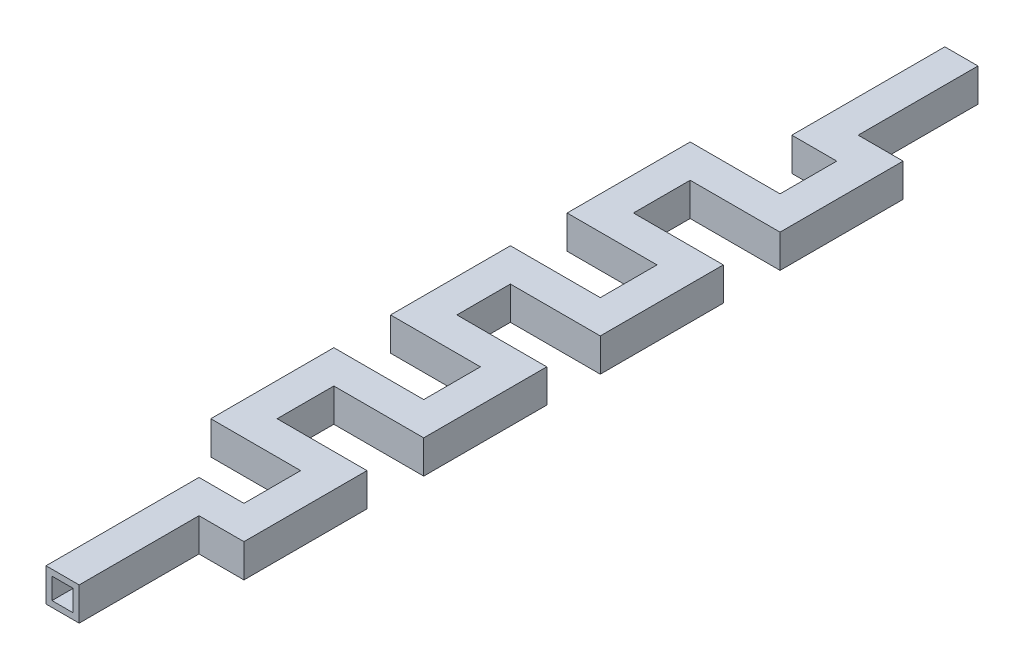
SolidWorks part; units mm, degrees
ref_plane "Front Plane" through (0, 0, 0) normal (0, 0, 1) x (1, 0, 0)
ref_plane "Top Plane" through (0, 0, 0) normal (0, 1, 0) x (1, 0, 0)
ref_plane "Right Plane" through (0, 0, 0) normal (1, 0, 0) x (0, 0, -1)
sketch "Sketch3" plane through (0, 0, 0) normal (0, 0, 1) x (1, 0, 0)
  line L1 (-1.3836, -1.3836) -> (1.3836, -1.3836)
  line L2 (-1.3836, -1.3836) -> (-1.3836, 1.3836)
  line L3 (-1.3836, 1.3836) -> (1.3836, 1.3836)
  line L4 (1.3836, -1.3836) -> (1.3836, 1.3836)
  line L5 (-1.3836, -1.3836) -> (1.3836, 1.3836) construction
  line L6 (-1.3836, 1.3836) -> (1.3836, -1.3836) construction
  point P0 (0, 0)
  dimension "D1" = 2.7671
  dimension "D2" = 2.7671
extrude "Boss-Extrude1" add sketch "Sketch3" along normal mid plane 10
sketch "Sketch4" plane through (1.3836, 0, 0) normal (1, 0, 0) x (0, 0, -1)
  line L1 (-2.2329, -1.3836) -> (-5, -1.3836)
  line L2 (-2.2329, -1.3836) -> (-2.2329, 1.3836)
  line L3 (-2.2329, 1.3836) -> (-5, 1.3836)
  line L4 (-5, -1.3836) -> (-5, 1.3836)
  line L5 (-2.2329, -1.3836) -> (-5, 1.3836) construction
  line L6 (-2.2329, 1.3836) -> (-5, -1.3836) construction
  line L7 (2.2329, -1.3836) -> (5, -1.3836)
  line L8 (2.2329, -1.3836) -> (2.2329, 1.3836)
  line L9 (2.2329, 1.3836) -> (5, 1.3836)
  line L10 (5, -1.3836) -> (5, 1.3836)
  line L11 (2.2329, -1.3836) -> (5, 1.3836) construction
  line L12 (2.2329, 1.3836) -> (5, -1.3836) construction
  point P0 (-3.6164, 0)
  point P6 (3.6164, 0)
  dimension "D1" = 2.7671
  dimension "D2" = 2.7672
  dimension "D3" = 2.7671
  dimension "D4" = 2.7672
extrude "Boss-Extrude2" add sketch "Sketch4" along normal blind 7.5
sketch "Sketch5" plane through (0, 0, 5) normal (0, 0, 1) x (1, 0, 0)
  line L1 (6.1164, -1.3836) -> (8.8836, -1.3836)
  line L2 (6.1164, -1.3836) -> (6.1164, 1.3836)
  line L3 (6.1164, 1.3836) -> (8.8836, 1.3836)
  line L4 (8.8836, -1.3836) -> (8.8836, 1.3836)
  line L5 (6.1164, -1.3836) -> (8.8836, 1.3836) construction
  line L6 (6.1164, 1.3836) -> (8.8836, -1.3836) construction
  point P0 (7.5, 0)
  dimension "D1" = 2.7671
extrude "Boss-Extrude3" add sketch "Sketch5" along normal blind 7.5
sketch "Sketch6" plane through (6.1164, 0, 0) normal (-1, 0, 0) x (0, 0, 1)
  line L1 (9.7329, -1.3836) -> (12.5, -1.3836)
  line L2 (9.7329, -1.3836) -> (9.7329, 1.3836)
  line L3 (9.7329, 1.3836) -> (12.5, 1.3836)
  line L4 (12.5, -1.3836) -> (12.5, 1.3836)
  line L5 (9.7329, -1.3836) -> (12.5, 1.3836) construction
  line L6 (9.7329, 1.3836) -> (12.5, -1.3836) construction
  point P0 (11.1164, 0)
  dimension "D1" = 2.7671
extrude "Boss-Extrude4" add sketch "Sketch6" along normal blind 7.5
sketch "Sketch7" plane through (0, 0, 12.5) normal (0, 0, 1) x (1, 0, 0)
  line L1 (-1.3836, -1.3836) -> (1.3836, -1.3836)
  line L2 (-1.3836, -1.3836) -> (-1.3836, 1.3836)
  line L3 (-1.3836, 1.3836) -> (1.3836, 1.3836)
  line L4 (1.3836, -1.3836) -> (1.3836, 1.3836)
  line L5 (-1.3836, -1.3836) -> (1.3836, 1.3836) construction
  line L6 (-1.3836, 1.3836) -> (1.3836, -1.3836) construction
  point P0 (0, 0)
extrude "Boss-Extrude5" add sketch "Sketch7" along normal blind 7.5
sketch "Sketch8" plane through (0, 0, -5) normal (0, 0, -1) x (-1, 0, 0)
  line L0 (-8.8836, 1.3836) -> (1.3836, 1.3836) construction
  line L1 (-8.8836, -1.3836) -> (-6.1164, -1.3836)
  line L2 (-8.8836, -1.3836) -> (-8.8836, 1.3836)
  line L3 (-8.8836, 1.3836) -> (-6.1164, 1.3836)
  line L4 (-6.1164, -1.3836) -> (-6.1164, 1.3836)
  line L5 (-8.8836, -1.3836) -> (-6.1164, 1.3836) construction
  line L6 (-8.8836, 1.3836) -> (-6.1164, -1.3836) construction
  line L7 (-8.8836, -1.3836) -> (-8.8836, 1.3836) construction
  point P0 (-7.5, 0)
  dimension "D1" = 2.7671
  dimension "D2" = 1.3836
extrude "Boss-Extrude6" add sketch "Sketch8" along normal blind 7.5
sketch "Sketch9" plane through (6.1164, 0, 0) normal (-1, 0, 0) x (0, 0, 1)
  line L1 (-9.7329, -1.3836) -> (-12.5, -1.3836)
  line L2 (-9.7329, -1.3836) -> (-9.7329, 1.3836)
  line L3 (-9.7329, 1.3836) -> (-12.5, 1.3836)
  line L4 (-12.5, -1.3836) -> (-12.5, 1.3836)
  line L5 (-9.7329, -1.3836) -> (-12.5, 1.3836) construction
  line L6 (-9.7329, 1.3836) -> (-12.5, -1.3836) construction
  point P0 (-11.1164, 0)
  dimension "D1" = 2.7671
extrude "Boss-Extrude7" add sketch "Sketch9" along normal blind 7.5
sketch "Sketch10" plane through (0, 0, -12.5) normal (0, 0, -1) x (-1, 0, 0)
  line L1 (-1.3836, -1.3836) -> (1.3836, -1.3836)
  line L2 (-1.3836, -1.3836) -> (-1.3836, 1.3836)
  line L3 (-1.3836, 1.3836) -> (1.3836, 1.3836)
  line L4 (1.3836, -1.3836) -> (1.3836, 1.3836)
  line L5 (-1.3836, -1.3836) -> (1.3836, 1.3836) construction
  line L6 (-1.3836, 1.3836) -> (1.3836, -1.3836) construction
  point P0 (0, 0)
extrude "Boss-Extrude8" add sketch "Sketch10" along normal blind 7.5
sketch "Sketch11" plane through (1.3836, 0, 0) normal (1, 0, 0) x (0, 0, -1)
  line L1 (17.2329, -1.3836) -> (20, -1.3836)
  line L2 (17.2329, -1.3836) -> (17.2329, 1.3836)
  line L3 (17.2329, 1.3836) -> (20, 1.3836)
  line L4 (20, -1.3836) -> (20, 1.3836)
  line L5 (17.2329, -1.3836) -> (20, 1.3836) construction
  line L6 (17.2329, 1.3836) -> (20, -1.3836) construction
  line L7 (-17.2329, -1.3836) -> (-20, -1.3836)
  line L8 (-17.2329, -1.3836) -> (-17.2329, 1.3836)
  line L9 (-17.2329, 1.3836) -> (-20, 1.3836)
  line L10 (-20, -1.3836) -> (-20, 1.3836)
  line L11 (-17.2329, -1.3836) -> (-20, 1.3836) construction
  line L12 (-17.2329, 1.3836) -> (-20, -1.3836) construction
  point P0 (18.6164, 0)
  point P6 (-18.6164, 0)
  dimension "D1" = 2.7671
  dimension "D2" = 2.7672
  dimension "D3" = 2.7671
  dimension "D4" = 2.7672
extrude "Boss-Extrude9" add sketch "Sketch11" along normal blind 7.5
sketch "Sketch12" plane through (0, 0, -20) normal (0, 0, -1) x (-1, 0, 0)
  line L0 (-8.8836, -1.3836) -> (-8.8836, 1.3836) construction
  line L1 (-6.1164, -1.3836) -> (-8.8836, -1.3836)
  line L2 (-6.1164, -1.3836) -> (-6.1164, 1.3836)
  line L3 (-6.1164, 1.3836) -> (-8.8836, 1.3836)
  line L4 (-8.8836, -1.3836) -> (-8.8836, 1.3836)
  line L5 (-6.1164, -1.3836) -> (-8.8836, 1.3836) construction
  line L6 (-6.1164, 1.3836) -> (-8.8836, -1.3836) construction
  point P0 (-7.5, 0)
  dimension "D1" = 2.7671
  dimension "D2" = 2.7672
extrude "Boss-Extrude10" add sketch "Sketch12" along normal blind 7.5
sketch "Sketch13" plane through (6.1164, 0, 0) normal (-1, 0, 0) x (0, 0, 1)
  line L1 (-24.7328, -1.3836) -> (-27.5, -1.3836)
  line L2 (-24.7328, -1.3836) -> (-24.7328, 1.3836)
  line L3 (-24.7328, 1.3836) -> (-27.5, 1.3836)
  line L4 (-27.5, -1.3836) -> (-27.5, 1.3836)
  line L5 (-24.7328, -1.3836) -> (-27.5, 1.3836) construction
  line L6 (-24.7328, 1.3836) -> (-27.5, -1.3836) construction
  point P0 (-26.1164, 0)
  dimension "D1" = 2.7671
extrude "Boss-Extrude11" add sketch "Sketch13" along normal blind 3.75
sketch "Sketch14" plane through (0, 0, -27.5) normal (0, 0, -1) x (-1, 0, 0)
  line L0 (-2.3664, 1.3836) -> (-8.8836, 1.3836) construction
  line L1 (-5.1336, -1.3836) -> (-2.3664, -1.3836)
  line L2 (-5.1336, -1.3836) -> (-5.1336, 1.3836)
  line L3 (-5.1336, 1.3836) -> (-2.3664, 1.3836)
  line L4 (-2.3664, -1.3836) -> (-2.3664, 1.3836)
  line L5 (-5.1336, -1.3836) -> (-2.3664, 1.3836) construction
  line L6 (-5.1336, 1.3836) -> (-2.3664, -1.3836) construction
  line L7 (-2.3664, 1.3836) -> (-2.3664, -1.3836) construction
  line L8 (-8.8836, -1.3836) -> (-2.3664, -1.3836) construction
  point P0 (-3.75, 0)
  dimension "D1" = 0
  dimension "D2" = 2.7671
  dimension "D3" = 0
extrude "Boss-Extrude12" add sketch "Sketch14" along normal blind 10
sketch "Sketch15" plane through (0, 0, 20) normal (0, 0, 1) x (1, 0, 0)
  line L1 (6.1164, -1.3836) -> (8.8836, -1.3836)
  line L2 (6.1164, -1.3836) -> (6.1164, 1.3836)
  line L3 (6.1164, 1.3836) -> (8.8836, 1.3836)
  line L4 (8.8836, -1.3836) -> (8.8836, 1.3836)
  line L5 (6.1164, -1.3836) -> (8.8836, 1.3836) construction
  line L6 (6.1164, 1.3836) -> (8.8836, -1.3836) construction
  point P0 (7.5, 0)
  dimension "D1" = 2.7671
extrude "Boss-Extrude13" add sketch "Sketch15" along normal blind 7.5
sketch "Sketch16" plane through (6.1164, 0, 0) normal (-1, 0, 0) x (0, 0, 1)
  line L1 (24.7328, -1.3836) -> (27.5, -1.3836)
  line L2 (24.7328, -1.3836) -> (24.7328, 1.3836)
  line L3 (24.7328, 1.3836) -> (27.5, 1.3836)
  line L4 (27.5, -1.3836) -> (27.5, 1.3836)
  line L5 (24.7328, -1.3836) -> (27.5, 1.3836) construction
  line L6 (24.7328, 1.3836) -> (27.5, -1.3836) construction
  point P0 (26.1164, 0)
  dimension "D1" = 2.7671
extrude "Boss-Extrude14" add sketch "Sketch16" along normal blind 3.75
sketch "Sketch17" plane through (0, 0, 27.5) normal (0, 0, 1) x (1, 0, 0)
  line L0 (6.1164, 1.3836) -> (-1.3836, 1.3836) construction
  line L1 (5.1336, -1.3836) -> (2.3664, -1.3836)
  line L2 (5.1336, -1.3836) -> (5.1336, 1.3836)
  line L3 (5.1336, 1.3836) -> (2.3664, 1.3836)
  line L4 (2.3664, -1.3836) -> (2.3664, 1.3836)
  line L5 (5.1336, -1.3836) -> (2.3664, 1.3836) construction
  line L6 (5.1336, 1.3836) -> (2.3664, -1.3836) construction
  point P0 (3.75, 0)
  dimension "D1" = 2.7671
extrude "Boss-Extrude15" add sketch "Sketch17" along normal blind 10
sketch "Sketch23" plane through (0, 1.3836, 0) normal (0, 1, 0) x (1, 0, 0)
  line L0 (2.8664, 37.5) -> (4.6336, 37.5)
  line L1 (2.3664, 37.5) -> (5.1336, 37.5) construction
  line L2 (4.6336, 37.5) -> (4.6336, 27)
  line L3 (4.6336, 27) -> (8.3836, 27)
  line L4 (8.3836, 27) -> (8.3836, 17.7329)
  line L5 (8.3836, 17.7329) -> (0.8836, 17.7329)
  line L6 (0.8836, 17.7329) -> (0.8836, 12)
  line L7 (0.8836, 12) -> (8.3836, 12)
  line L8 (8.3836, 12) -> (8.3836, 2.7329)
  line L9 (8.3836, 2.7329) -> (0.8836, 2.7328)
  line L10 (0.8836, 2.7328) -> (0.8836, -2.7329)
  line L11 (0.8836, -2.7329) -> (8.3836, -2.7329)
  line L12 (8.3836, -2.7329) -> (8.3836, -12)
  line L13 (8.3836, -12) -> (0.8836, -12)
  line L14 (0.8836, -12) -> (0.8836, -17.7329)
  line L15 (0.8836, -17.7329) -> (8.3836, -17.7329)
  line L16 (8.3836, -17.7329) -> (8.3836, -27)
  line L17 (8.3836, -27) -> (4.6336, -27)
  line L18 (4.6336, -27) -> (4.6336, -37.5)
  line L19 (5.1336, -37.5) -> (2.3664, -37.5) construction
  line L20 (4.6336, -37.5) -> (2.8664, -37.5)
  line L21 (2.8664, -37.5) -> (2.8664, -25.2329)
  line L22 (2.8664, -25.2329) -> (6.6164, -25.2329)
  line L23 (6.6164, -25.2329) -> (6.6164, -19.5)
  line L24 (6.6164, -19.5) -> (-0.8836, -19.5)
  line L25 (-0.8836, -19.5) -> (-0.8836, -10.2329)
  line L26 (-0.8836, -10.2329) -> (6.6164, -10.2329)
  line L27 (6.6164, -10.2329) -> (6.6164, -4.5)
  line L28 (6.6164, -4.5) -> (-0.8836, -4.5)
  line L29 (-0.8836, -4.5) -> (-0.8836, 4.5)
  line L30 (-0.8836, 4.5) -> (6.6164, 4.5)
  line L31 (6.6164, 4.5) -> (6.6164, 10.2329)
  line L32 (6.6164, 10.2329) -> (-0.8836, 10.2329)
  line L33 (-0.8836, 10.2329) -> (-0.8836, 19.5)
  line L34 (-0.8836, 19.5) -> (6.6164, 19.5)
  line L35 (6.6164, 19.5) -> (6.6164, 25.2329)
  line L36 (6.6164, 25.2329) -> (2.8664, 25.2329)
  line L37 (2.8664, 25.2329) -> (2.8664, 37.5)
  line L39 (2.3664, 24.7328) -> (6.1164, 24.7328) construction
  line L40 (5.1336, 27.5) -> (8.8836, 27.5) construction
  line L42 (8.8836, 27.5) -> (8.8836, 17.2329) construction
  line L43 (6.1164, 24.7328) -> (6.1164, 20) construction
  line L44 (8.8836, 17.2329) -> (1.3836, 17.2329) construction
  line L45 (-1.3836, 20) -> (6.1164, 20) construction
  line L46 (1.3836, 17.2329) -> (1.3836, 12.5) construction
  line L47 (-1.3836, 9.7329) -> (-1.3836, 20) construction
  line L48 (1.3836, 12.5) -> (8.8836, 12.5) construction
  line L49 (-1.3836, 9.7329) -> (6.1164, 9.7329) construction
  line L50 (8.8836, 12.5) -> (8.8836, 2.2329) construction
  line L51 (6.1164, 9.7329) -> (6.1164, 5) construction
  line L52 (8.8836, 2.2329) -> (1.3836, 2.2328) construction
  line L53 (6.1164, 5) -> (-1.3836, 5) construction
  line L54 (-1.3836, -5) -> (-1.3836, 5) construction
  line L55 (1.3836, -2.2329) -> (1.3836, 2.2328) construction
  line L56 (8.8836, -2.2329) -> (1.3836, -2.2329) construction
  line L57 (6.1164, -5) -> (-1.3836, -5) construction
  line L58 (8.8836, -2.2329) -> (8.8836, -12.5) construction
  line L59 (6.1164, -9.7329) -> (6.1164, -5) construction
  line L60 (8.8836, -12.5) -> (1.3836, -12.5) construction
  line L61 (-1.3836, -9.7329) -> (6.1164, -9.7329) construction
  line L62 (-1.3836, -20) -> (-1.3836, -9.7329) construction
  line L63 (1.3836, -17.2329) -> (1.3836, -12.5) construction
  line L64 (8.8836, -17.2329) -> (1.3836, -17.2329) construction
  line L65 (6.1164, -20) -> (-1.3836, -20) construction
  line L66 (8.8836, -17.2329) -> (8.8836, -27.5) construction
  line L67 (6.1164, -24.7328) -> (6.1164, -20) construction
  line L68 (8.8836, -27.5) -> (5.1336, -27.5) construction
  line L69 (2.3664, -24.7328) -> (6.1164, -24.7328) construction
  line L70 (2.3664, -37.5) -> (2.3664, -24.7328) construction
  line L71 (5.1336, -37.5) -> (5.1336, -27.5) construction
  point P33 (3.75, 37.5)
  dimension "D1" = 1.7671
  dimension "D2" = 1.3836
  dimension "D3" = 0.5
  dimension "D4" = 0.5
  dimension "D5" = 0.5
  dimension "D6" = 0.5
  dimension "D7" = 0.5
  dimension "D8" = 0.5
  dimension "D9" = 0.5
  dimension "D10" = 0.5
  dimension "D11" = 0.5
  dimension "D12" = 0.5
  dimension "D13" = 0.5
  dimension "D14" = 0.5
  dimension "D15" = 0.5
  dimension "D16" = 0.5
  dimension "D17" = 0.5
  dimension "D18" = 0.5
  dimension "D19" = 0.5
  dimension "D20" = 0.5
  dimension "D21" = 0.5
  dimension "D22" = 0.5
  dimension "D23" = 0.5
  dimension "D24" = 0.5
  dimension "D25" = 0.5
  dimension "D26" = 0.5
  dimension "D27" = 0.5
  dimension "D28" = 0.5
  dimension "D29" = 0.5
  dimension "D30" = 0.5
  dimension "D31" = 0.5
  dimension "D32" = 0.5
  dimension "D33" = 0.5
  dimension "D34" = 0.5
extrude "Cut-Extrude3" cut sketch "Sketch23" against normal blind 1.7671 from offset 0.5
